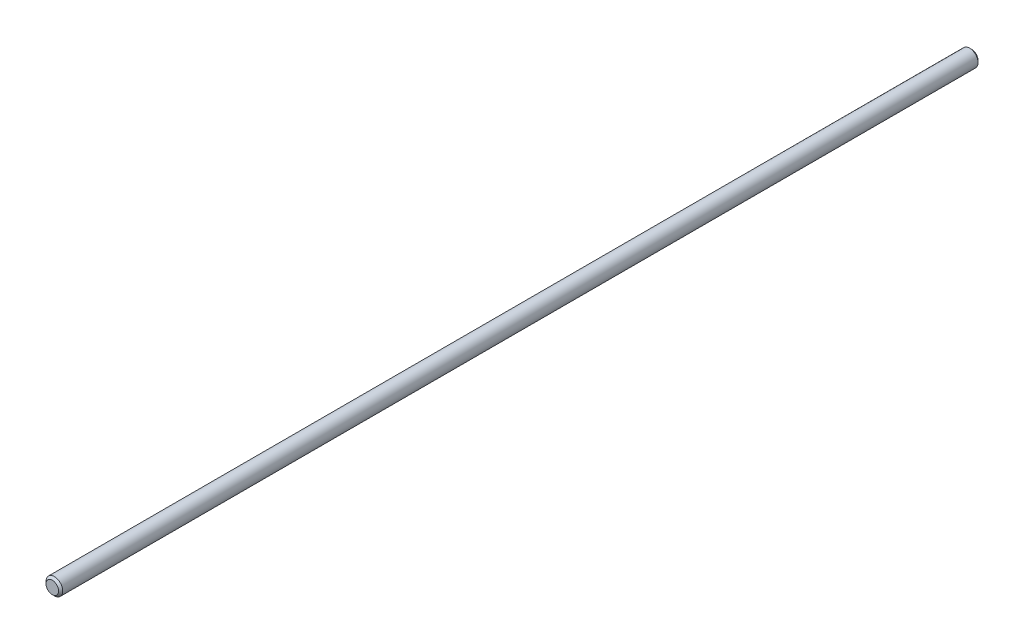
SolidWorks part; units mm, degrees
ref_plane "Front Plane" through (0, 0, 0) normal (0, 0, 1) x (1, 0, 0)
ref_plane "Top Plane" through (0, 0, 0) normal (0, 1, 0) x (1, 0, 0)
ref_plane "Right Plane" through (0, 0, 0) normal (1, 0, 0) x (0, 0, -1)
sketch "Sketch1" plane through (0, 0, 0) normal (0, 0, 1) x (1, 0, 0)
  circle A0 centre (0, 0) radius 2
  dimension "D1" = 4
extrude "Boss-Extrude1" add sketch "Sketch1" along normal mid plane 220
chamfer "Chamfer1" distance 0.5 angle 45 2 edges at (2, 0, -110) (2, 0, 110)
